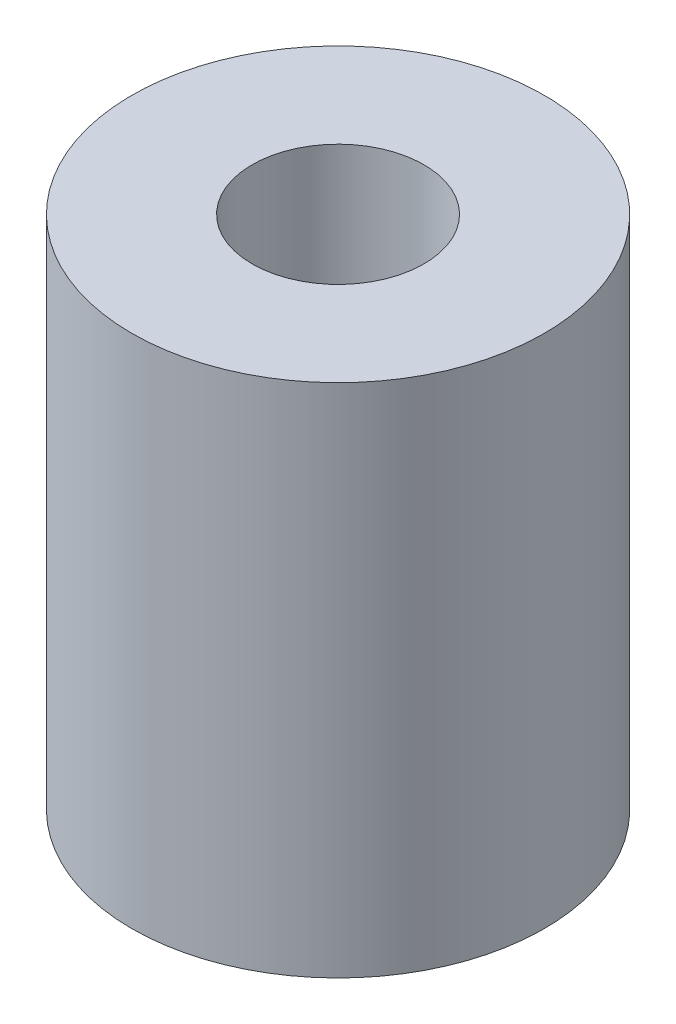
SolidWorks part; units mm, degrees
material "AISI 304"
ref_plane "Front" through (0, 0, 0) normal (0, 0, 1) x (1, 0, 0)
ref_plane "Top" through (0, 0, 0) normal (0, 1, 0) x (1, 0, 0)
ref_plane "Right" through (0, 0, 0) normal (1, 0, 0) x (0, 0, -1)
sketch "Sketch1" plane through (0, 0, 0) normal (0, 1, 0) x (1, 0, 0)
  circle A0 centre (0, 0) radius 6
  dimension "D1" = 12
extrude "Boss-Extrude1" add sketch "Sketch1" along normal blind 15
sketch "Sketch4" plane through (0, 15, 0) normal (0, 1, 0) x (1, 0, 0)
  circle A0 centre (0, 0) radius 2.5
  dimension "D1" = 5
extrude "Cut-Extrude2" cut sketch "Sketch4" against normal through all
